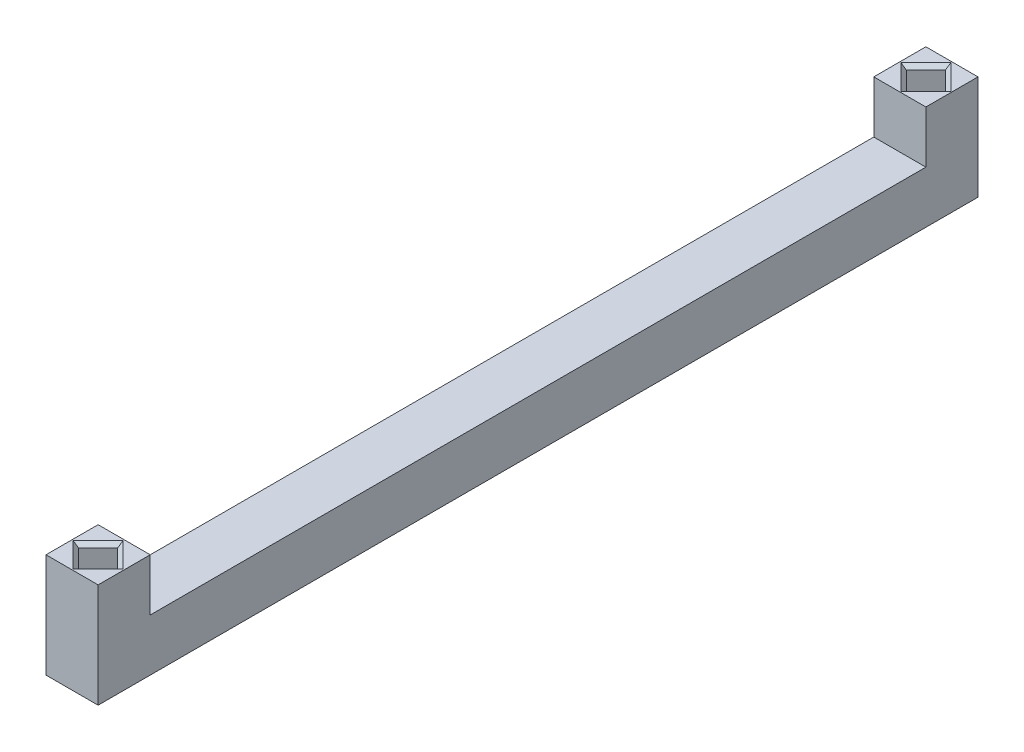
SolidWorks part; units mm, degrees
ref_plane "Front Plane" through (0, 0, 0) normal (0, 0, 1) x (1, 0, 0)
ref_plane "Top Plane" through (0, 0, 0) normal (0, 1, 0) x (1, 0, 0)
ref_plane "Right Plane" through (0, 0, 0) normal (1, 0, 0) x (0, 0, -1)
sketch "Sketch1" plane through (0, 0, 0) normal (1, 0, 0) x (0, 0, -1)
  line L0 (-71.4667, 8.4667) -> (-71.4667, -8.4667)
  line L1 (-71.4667, -8.4667) -> (71.4667, -8.4667)
  line L2 (71.4667, -8.4667) -> (71.4667, 8.4667)
  line L3 (71.4667, 8.4667) -> (63, 8.4667)
  line L4 (63, 8.4667) -> (63, 0)
  line L5 (63, 0) -> (-63, 0)
  line L6 (-63, 0) -> (-63, 8.4667)
  line L7 (-63, 8.4667) -> (-71.4667, 8.4667)
  point P0 (0, 0)
  dimension "D1" = 8.4667
  dimension "D2" = 16.9333
  dimension "D3" = 142.9333
extrude "Boss-Extrude1" add sketch "Sketch1" along normal blind 8.4667
sketch "Sketch2" plane through (0, 8.4667, 0) normal (0, 1, 0) x (1, 0, 0)
  line L0 (1.0583, -67.2333) -> (4.2333, -64.0583)
  line L1 (1.0583, -67.2333) -> (4.2333, -70.4083)
  line L2 (4.2333, -64.0583) -> (7.4083, -67.2333)
  line L3 (4.2333, -70.4083) -> (7.4083, -67.2333)
  line L4 (1.0583, -67.2333) -> (7.4083, -67.2333) construction
  line L5 (4.2333, -64.0583) -> (4.2333, -70.4083) construction
  line L6 (1.0583, 67.2333) -> (4.2333, 70.4083)
  line L7 (1.0583, 67.2333) -> (4.2333, 64.0583)
  line L8 (4.2333, 70.4083) -> (7.4083, 67.2333)
  line L9 (4.2333, 64.0583) -> (7.4083, 67.2333)
  line L10 (1.0583, 67.2333) -> (7.4083, 67.2333) construction
  line L11 (4.2333, 70.4083) -> (4.2333, 64.0583) construction
  line L12 (8.4667, 71.4667) -> (0, 71.4667) construction
  line L13 (8.4667, 71.4667) -> (8.4667, 63) construction
  line L14 (8.4667, -63) -> (8.4667, -71.4667) construction
  line L15 (8.4667, -71.4667) -> (0, -71.4667) construction
  point P1 (4.2333, -67.2333)
  point P2 (4.2333, 67.2333)
  point P8 (4.2333, 71.4667)
  point P15 (8.4667, 67.2333)
  point P18 (8.4667, -67.2333)
  point P21 (4.2333, -71.4667)
  dimension "D1" = 6.35
  dimension "D2" = 6.35
extrude "Cut-Extrude1" cut sketch "Sketch2" against normal blind 5.08
chamfer "Chamfer1" distance 0.635 angle 45 16 edges at (2.6458, 3.3867, -68.8208) (5.8208, 3.3867, -68.8208) (5.8208, 3.3867, -65.6458) (2.6458, 3.3867, -65.6458) (2.6458, 3.3867, 65.6458) (5.8208, 3.3867, 65.6458) (5.8208, 3.3867, 68.8208) (2.6458, 3.3867, 68.8208) (2.6458, 8.4667, -68.8208) (2.6458, 8.4667, -65.6458) (5.8208, 8.4667, -65.6458) (5.8208, 8.4667, -68.8208) (2.6458, 8.4667, 65.6458) (2.6458, 8.4667, 68.8208) (5.8208, 8.4667, 68.8208) (5.8208, 8.4667, 65.6458)
